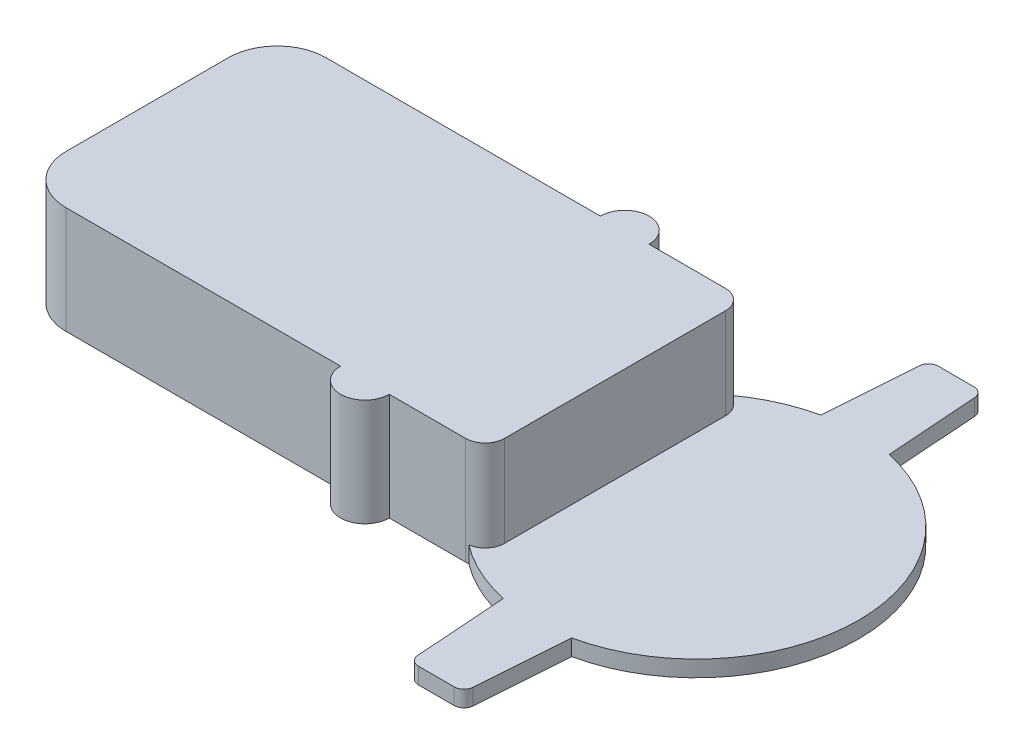
SolidWorks part; units mm, degrees
ref_plane "Front Plane" through (0, 0, 0) normal (0, 0, 1) x (1, 0, 0)
ref_plane "Top Plane" through (0, 0, 0) normal (0, 1, 0) x (1, 0, 0)
ref_plane "Right Plane" through (0, 0, 0) normal (1, 0, 0) x (0, 0, -1)
sketch "Sketch1" plane through (0, 0, 0) normal (0, 1, 0) x (1, 0, 0)
  line L0 (-50, 0) -> (50, 0) construction
  line L1 (-10.5, 48.8851) -> (-8.5, 77.2113)
  line L2 (-5.5074, 80) -> (5.5074, 80)
  line L3 (0, 0) -> (0, 51.3811) construction
  line L4 (10.5, 48.8851) -> (8.5, 77.2113)
  line L5 (10.5, -48.8851) -> (8.5, -77.2113)
  line L6 (-5.5074, -80) -> (5.5074, -80)
  line L7 (-10.5, -48.8851) -> (-8.5, -77.2113)
  arc A0 (-10.5, 48.8851) -> (-10.5, -48.8851) centre (0, 0) ccw
  arc A1 (-8.5, 77.2113) -> (-5.5074, 80) centre (-5.5074, 77) cw
  arc A2 (8.5, 77.2113) -> (5.5074, 80) centre (5.5074, 77) ccw
  arc A3 (8.5, -77.2113) -> (5.5074, -80) centre (5.5074, -77) cw
  arc A4 (-8.5, -77.2113) -> (-5.5074, -80) centre (-5.5074, -77) ccw
  arc A5 (10.5, -48.8851) -> (10.5, 48.8851) centre (0, 0) ccw
  point P5 (16.7625, 51.3811)
  point P10 (8.8272, 48.4526)
  point P13 (0, 80)
  point P15 (10.2006, 68.5961)
  point P23 (0, -80)
  point P26 (16.158, 47.3172)
  point P27 (9.7738, 66.1691)
  point P28 (11.0414, 71.1743)
  point P29 (0, 0)
  dimension "D1" = 50
  dimension "D5" = 3
  dimension "D2" = 17
  dimension "D3" = 21
  dimension "D4" = 160
extrude "Boss-Extrude1" add sketch "Sketch1" along normal blind 5
sketch "Sketch2" plane through (0, 0, 0) normal (0, 1, 0) x (1, 0, 0)
  line L0 (-169, 0) -> (-25, 0) construction
  line L1 (-154, -40) -> (-69.5, -40)
  line L2 (-169, -25) -> (-169, 25)
  line L3 (-154, 40) -> (-69.5, 40)
  line L4 (-25, -34) -> (-25, 34)
  line L5 (-169, -40) -> (-25, 40) construction
  line L6 (-169, 40) -> (-25, -40) construction
  line L7 (-54.5, 40) -> (-31, 40)
  line L8 (-54.5, -40) -> (-31, -40)
  arc A0 (-31, 40) -> (-25, 34) centre (-31, 34) cw
  arc A1 (-31, -40) -> (-25, -34) centre (-31, -34) ccw
  arc A2 (-154, -40) -> (-169, -25) centre (-154, -25) cw
  arc A3 (-169, 25) -> (-154, 40) centre (-154, 25) cw
  arc A4 (-54.5, 40) -> (-69.5, 40) centre (-62, 40) ccw
  arc A5 (-54.5, -40) -> (-69.5, -40) centre (-62, -40) cw
  point P0 (-97, 0)
  dimension "D4" = 6
  dimension "D5" = 15
  dimension "D6" = 7.5
  dimension "D1" = 144
  dimension "D2" = 169
  dimension "D3" = 80
  dimension "D7" = 107
extrude "Boss-Extrude2" add sketch "Sketch2" along normal blind 33
